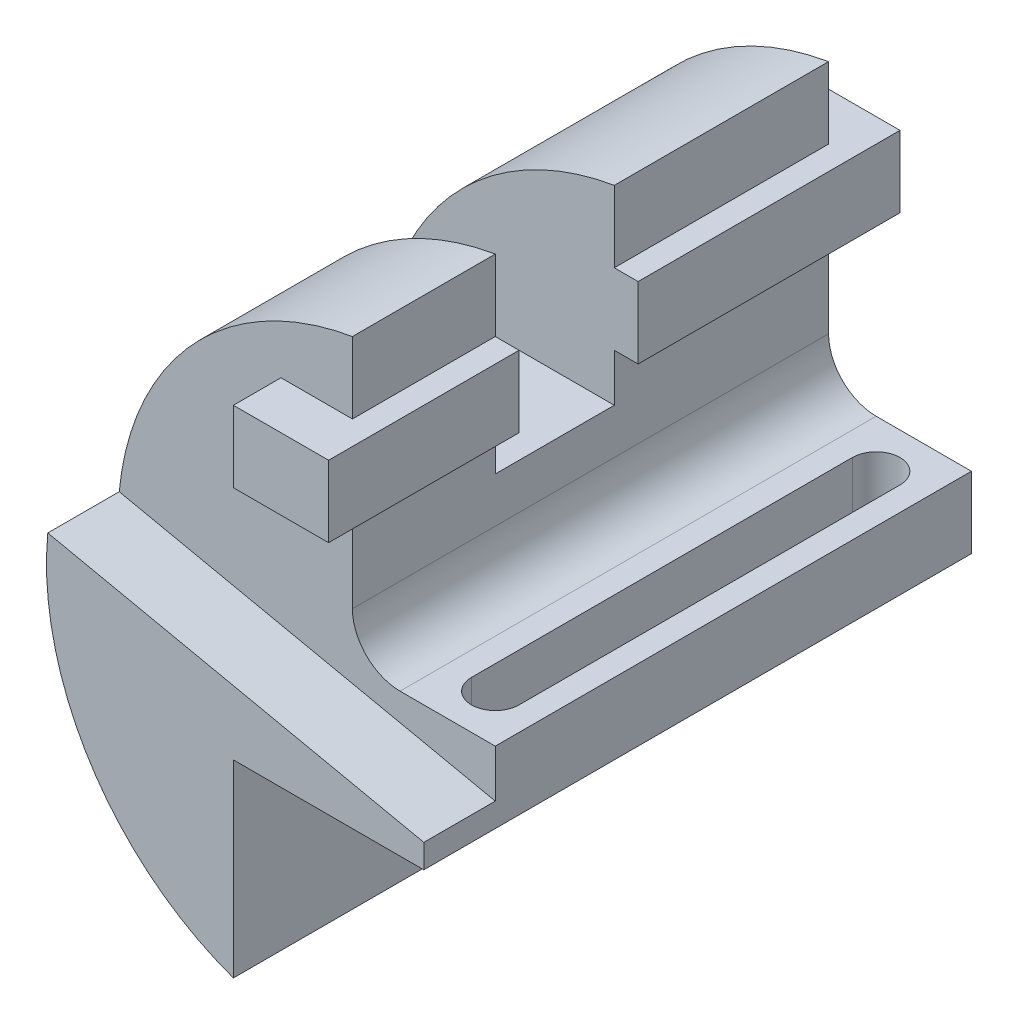
SolidWorks part; units mm, degrees
material "Alliage 1060"
ref_plane "Plan de face" through (0, 0, 0) normal (0, 0, 1) x (1, 0, 0)
ref_plane "Plan de dessus" through (0, 0, 0) normal (0, 1, 0) x (1, 0, 0)
ref_plane "Plan de droite" through (0, 0, 0) normal (1, 0, 0) x (0, 0, -1)
sketch "Esquisse1" plane through (0, 0, 0) normal (0, 0, 1) x (1, 0, 0)
  line L0 (-10, 58.4) -> (-10, 8.9)
  line L1 (0, -1.1) -> (20, -1.1)
  line L2 (20, -1.1) -> (20, -16.1)
  line L3 (20, -16.1) -> (-20, -16.1)
  line L4 (-20, -16.1) -> (-20, -55.7724)
  line L5 (0, 61.6077) -> (0, -61.6077) construction
  line L6 (-90.3006, 0) -> (90.3006, 0) construction
  arc A0 (-10, 58.4) -> (-20, -55.7724) centre (0, 0) ccw
  arc A1 (-10, 8.9) -> (0, -1.1) centre (0, 8.9) ccw
  point P14 (-10, -1.1)
  dimension "D5" = 59.25
  dimension "D7" = 10
  dimension "D1" = 10
  dimension "D2" = 20
  dimension "D3" = 40
  dimension "D4" = 15
  dimension "D6" = 59.5
extrude "Boss.-Extru.1" add sketch "Esquisse1" along normal blind 115
sketch "Esquisse2" plane through (0, 0, 115) normal (0, 0, 1) x (1, 0, 0)
  line L0 (20, -11.1) -> (-58.9764, 5.687)
  line L1 (20, -16.1) -> (20, -1.1) construction
  line L7 (-20, -55.7724) -> (-20, -16.1)
  line L8 (-20, -16.1) -> (20, -16.1)
  line L9 (20, -16.1) -> (20, -1.1)
  line L10 (20, -1.1) -> (0, -1.1)
  line L11 (-10, 8.9) -> (-10, 58.4)
  line L14 (20, -11.1) -> (20, -1.1)
  line L15 (20, -1.1) -> (0, -1.1)
  line L16 (-10, 8.9) -> (-10, 58.4)
  arc A0 (-10, 58.4) -> (-20, -55.7724) centre (0, 0) ccw construction
  arc A3 (-10, 58.4) -> (-20, -55.7724) centre (0, 0) ccw
  arc A4 (-10, 8.9) -> (0, -1.1) centre (0, 8.9) ccw
  arc A5 (-10, 58.4) -> (-58.9764, 5.687) centre (0, 0) ccw
  arc A6 (-10, 8.9) -> (0, -1.1) centre (0, 8.9) ccw
  dimension "D1" = 5
  dimension "D2" = 78
  dimension "D3" = 0
extrude "Enlèv. mat.-Extru.1" cut sketch "Esquisse2" against normal blind 15
sketch "Esquisse3" plane through (0, 0, 100) normal (0, 0, 1) x (1, 0, 0)
  line L0 (-10, 8.9) -> (-10, 58.4) construction
  line L1 (-25, 43.4) -> (-5, 43.4)
  line L2 (-25, 43.4) -> (-25, 28.4)
  line L3 (-25, 28.4) -> (-5, 28.4)
  line L4 (-5, 43.4) -> (-5, 28.4)
  dimension "D1" = 5
  dimension "D2" = 15
  dimension "D3" = 15
  dimension "D4" = 15
extrude "Boss.-Extru.2" add sketch "Esquisse3" against normal offset from surface (120 mm away) 10 from offset 10
sketch "Esquisse4" plane through (-5, 0, 0) normal (1, 0, 0) x (0, 0, -1)
  line L0 (-100, 58.4) -> (0, 58.4) construction
  line L1 (-70, 58.4) -> (-45, 58.4)
  line L2 (-70, 58.4) -> (-70, 18.4)
  line L3 (-70, 18.4) -> (-45, 18.4)
  line L4 (-45, 58.4) -> (-45, 18.4)
  line L5 (-100, 43.4) -> (-100, 58.4) construction
  dimension "D3" = 40
  dimension "D1" = 30
  dimension "D2" = 25
extrude "Enlèv. mat.-Extru.2" cut sketch "Esquisse4" against normal through all
sketch "Esquisse5" plane through (0, -1.1, 0) normal (0, 1, 0) x (1, 0, 0)
  line L0 (10, 0) -> (10, -100) construction
  line L1 (20, 0) -> (0, 0) construction
  line L2 (20, -100) -> (0, -100) construction
  line L3 (10, -10) -> (10, -90) construction
  line L4 (15, -10) -> (15, -90)
  line L5 (5, -10) -> (5, -90)
  line L6 (-58.9764, -100) -> (20, -100) construction
  arc A0 (15, -10) -> (5, -10) centre (10, -10) ccw
  arc A1 (5, -90) -> (15, -90) centre (10, -90) ccw
  point P8 (10, -50)
  dimension "D1" = 5
  dimension "D2" = 80
  dimension "D3" = 10
extrude "Enlèv. mat.-Extru.3" cut sketch "Esquisse5" against normal through all
equation "\"A\"= 59.25"
equation "\"B\"= 59.5"
equation "\"C\"= 25"
equation "\"D5@Esquisse1\"=\"A\""
equation "\"D6@Esquisse1\"=\"B\""
equation "\"D2@Esquisse4\"=\"C\""
